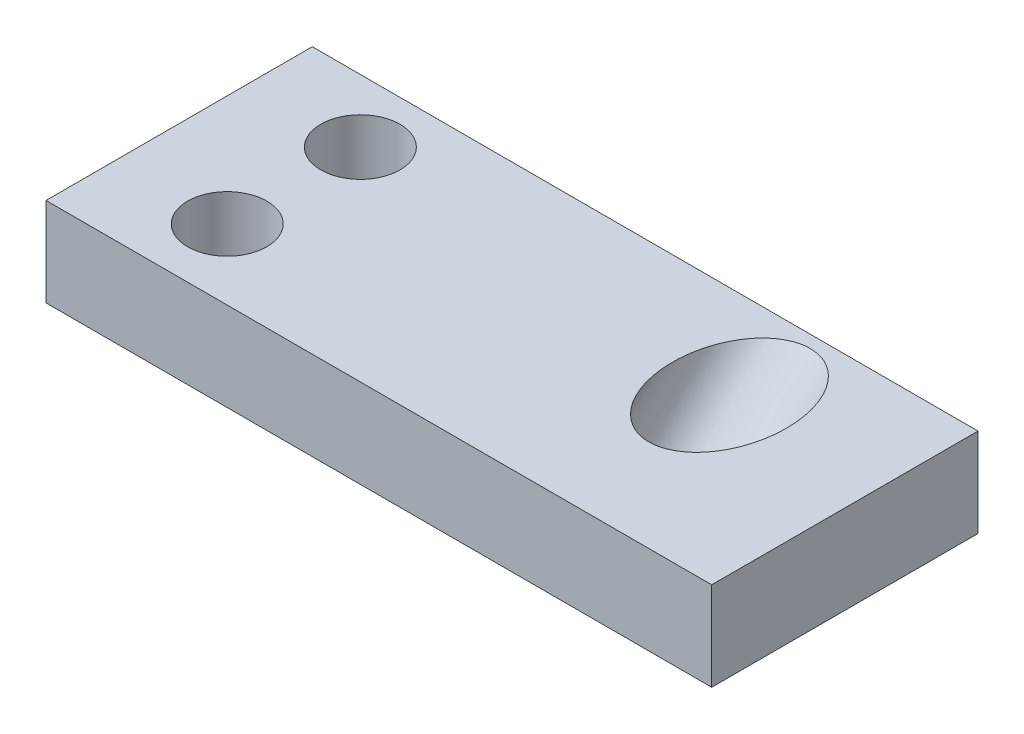
SolidWorks part; units mm, degrees
ref_plane "Piano frontale" through (0, 0, 0) normal (0, 0, 1) x (1, 0, 0)
ref_plane "Piano superiore" through (0, 0, 0) normal (0, 1, 0) x (1, 0, 0)
ref_plane "Piano destro" through (0, 0, 0) normal (1, 0, 0) x (0, 0, -1)
sketch "Schizzo1" plane through (0, 0, 0) normal (0, 1, 0) x (1, 0, 0)
  line L1 (-15, 6) -> (15, 6)
  line L2 (-15, 6) -> (-15, -6)
  line L3 (-15, -6) -> (15, -6)
  line L4 (15, 6) -> (15, -6)
  line L5 (-15, 6) -> (15, -6) construction
  line L6 (-15, -6) -> (15, 6) construction
  circle A0 centre (-10, 3.1666) radius 1.785
  circle A1 centre (-10, -2.8334) radius 1.785
  point P0 (0, 0)
  dimension "D3" = 5
  dimension "D4" = 6
  dimension "D1" = 12
  dimension "D2" = 30
extrude "Estrusione-Estrusione1" add sketch "Schizzo1" along normal blind 4
sketch "Schizzo4" plane through (0, 4, 0) normal (0, 1, 0) x (1, 0, 0)
  line L0 (-5.6285, 1.8) -> (20.9928, 1.8) construction
  line L1 (-15, -6) -> (15, -6) construction
  dimension "D1" = 7.8
ref_plane "Piano2" through (0, 2.9, -2.9) normal (0, -0.7071, 0.7071) x (1, 0, 0)
sketch "Schizzo3" plane through (0, 2.9, -2.9) normal (0, -0.7071, 0.7071) x (1, 0, 0)
  line L0 (-10, -3.5013) -> (-10, 23.8816) construction
  line L2 (-5.6285, 1.5556) -> (20.9928, 1.5556) construction
  line L4 (15, 7.0711) -> (15, -1.4142) construction
  circle A0 centre (8, 1.5556) radius 2.575
  ellipse E0 centre (-10, -2.2391) end of major axis (-8.215, -2.2391) minor radius 1.2622 construction
  dimension "D1" = 18
  dimension "D2" = 5.15
  dimension "D4" = 7
extrude "Taglio-Estrusione2" cut sketch "Schizzo3" against normal mid plane 50
